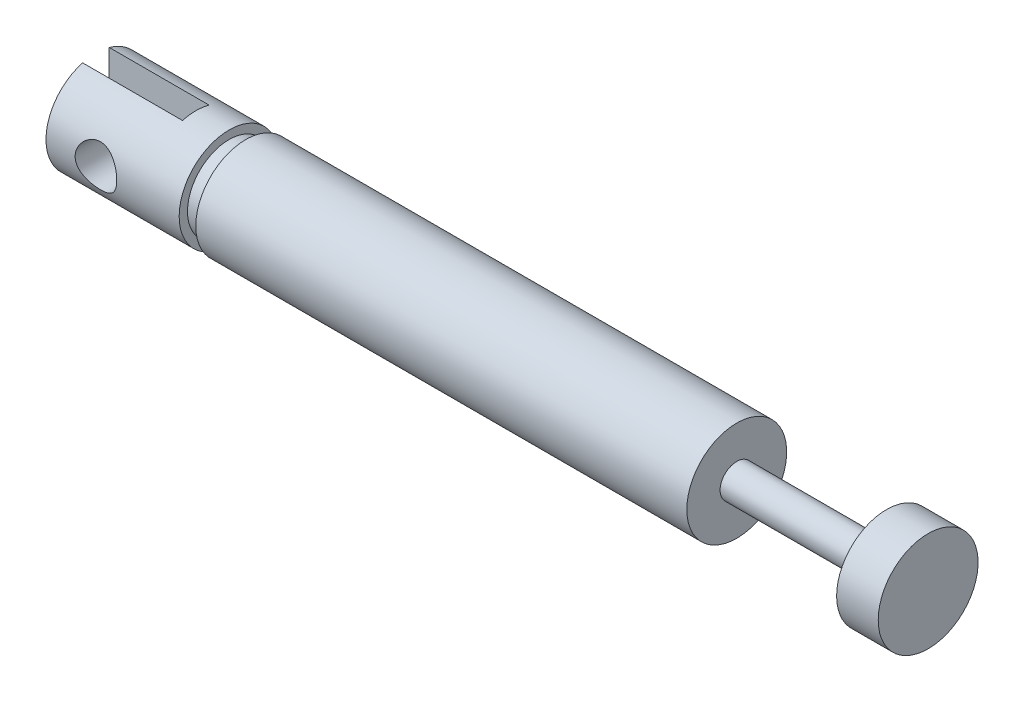
SolidWorks part; units mm, degrees
ref_plane "Plan de face" through (0, 0, 0) normal (0, 0, 1) x (1, 0, 0)
ref_plane "Plan de dessus" through (0, 0, 0) normal (0, 1, 0) x (1, 0, 0)
ref_plane "Plan de droite" through (0, 0, 0) normal (1, 0, 0) x (0, 0, -1)
sketch "Esquisse1" plane through (0, 0, 0) normal (0, 0, 1) x (1, 0, 0)
  line L0 (-17.6095, 0) -> (25.1576, 0) construction
  line L5 (38.5, 3) -> (38.5, 1)
  line L6 (38.5, 1) -> (47.5, 1)
  line L7 (47.5, 1) -> (47.5, 3)
  line L8 (47.5, 3) -> (50, 3)
  line L9 (50, 3) -> (50, 0)
  line L10 (8, 3) -> (8, 2.5)
  line L11 (8, 2.5) -> (9, 2.5)
  line L12 (9, 2.5) -> (9, 3)
  line L14 (0, 3) -> (8, 3)
  line L15 (9, 3) -> (38.5, 3)
  line L16 (0, 3) -> (0, 0)
  line L18 (0, 0) -> (50, 0)
  dimension "D1" = 3
  dimension "D2" = 0.5
  dimension "D3" = 11.5
  dimension "D4" = 9
  dimension "D5" = 50
  dimension "D6" = 1
  dimension "D7" = 3
  dimension "D8" = 8
  dimension "D9" = 1
  dimension "D10" = 0.5
revolve "Révolution3" add sketch "Esquisse1" angle 360 about L18
sketch "Esquisse6" plane through (0, 0, 0) normal (0, 0, 1) x (1, 0, 0)
  line L0 (0, 0) -> (6, 0) construction
  line L1 (0, 3) -> (0, -3) construction
  circle A0 centre (3, 0) radius 1.25
  dimension "D1" = 2.5
  dimension "D2" = 3
extrude "Enlèv. mat.-Extru.5" cut sketch "Esquisse6" against normal through all and the other way through all
sketch "Esquisse8" plane through (0, 0, 0) normal (0, 1, 0) x (1, 0, 0)
  line L1 (0, 0) -> (6, 0)
  line L2 (0, 0) -> (0, -0.8)
  line L3 (0, -0.8) -> (6, -0.8)
  line L4 (6, 0) -> (6, -0.8)
  line L5 (0, 0) -> (6, 0)
  line L6 (0, 0) -> (0, 0.8)
  line L7 (0, 0.8) -> (6, 0.8)
  line L8 (6, 0) -> (6, 0.8)
  dimension "D1" = 6
  dimension "D2" = 0.8
  dimension "D3" = 0.8
extrude "Enlèv. mat.-Extru.7" cut sketch "Esquisse8" against normal through all and the other way through all contours L1 L8 L7 L6 | L4 L1 L2 L3
